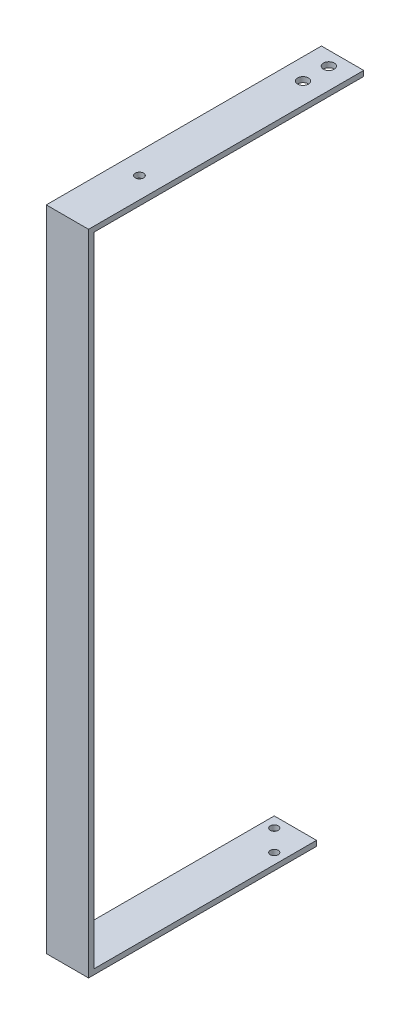
SolidWorks part; units mm, degrees
ref_plane "Alzado" through (0, 0, 0) normal (0, 0, 1) x (1, 0, 0)
ref_plane "Planta" through (0, 0, 0) normal (0, 1, 0) x (1, 0, 0)
ref_plane "Vista lateral" through (0, 0, 0) normal (1, 0, 0) x (0, 0, -1)
sketch "Croquis1" plane through (0, 0, 0) normal (0, 0, 1) x (1, 0, 0)
  line L1 (25.4, -3.155) -> (-25.4, -3.155)
  line L2 (25.4, -3.155) -> (25.4, 3.155)
  line L3 (25.4, 3.155) -> (-25.4, 3.155)
  line L4 (-25.4, -3.155) -> (-25.4, 3.155)
  line L5 (25.4, -3.155) -> (-25.4, 3.155) construction
  line L6 (25.4, 3.155) -> (-25.4, -3.155) construction
  point P0 (0, 0)
  dimension "D1" = 50.8
  dimension "D2" = 6.31
extrude "Saliente-Extruir1" add sketch "Croquis1" along normal blind 273.99
sketch "Croquis2" plane through (0, 3.155, 0) normal (0, 1, 0) x (1, 0, 0)
  line L0 (-25.4, -273.99) -> (25.4, -273.99)
  line L1 (25.4, -273.99) -> (25.4, -267.68)
  line L2 (25.4, -273.99) -> (25.4, 0) construction
  line L3 (25.4, -267.68) -> (-25.4, -267.68)
  line L4 (-25.4, -273.99) -> (-25.4, 0) construction
  line L5 (-25.4, -267.68) -> (-25.4, -273.99)
  dimension "D1" = 6.31
extrude "Saliente-Extruir2" add sketch "Croquis2" along normal blind 772.95
sketch "Croquis3" plane through (0, 0, 267.68) normal (0, 0, -1) x (-1, 0, 0)
  line L0 (25.4, 776.105) -> (25.4, 769.795)
  line L1 (25.4, 776.105) -> (25.4, 3.155) construction
  line L2 (25.4, 769.795) -> (-25.4, 769.795)
  line L3 (-25.4, 776.105) -> (-25.4, 3.155) construction
  line L4 (-25.4, 769.795) -> (-25.4, 776.105)
  line L5 (-25.4, 776.105) -> (25.4, 776.105)
  dimension "D1" = 6.31
extrude "Saliente-Extruir3" add sketch "Croquis3" along normal blind 324.39
sketch "Croquis4" plane through (0, -3.155, 0) normal (0, -1, 0) x (1, 0, 0)
  line L0 (25.4, 0) -> (-25.4, 0) construction
  line L1 (-25.4, 0) -> (-25.4, 50.8) construction
  line L2 (-25.4, 273.99) -> (-25.4, 0) construction
  line L3 (-25.4, 50.8) -> (25.4, 50.8) construction
  line L4 (25.4, 273.99) -> (25.4, 0) construction
  line L5 (25.4, 50.8) -> (25.4, 0) construction
  line L6 (25.4, 50.8) -> (-25.4, 0) construction
  line L7 (0, 25.4) -> (-25.4, 25.4) construction
  line L8 (-25.4, 25.4) -> (0, 25.4) construction
  line L9 (0, 25.4) -> (-25.4, 0) construction
  line L10 (-12.7, 12.7) -> (-20.119, 12.7) construction
  line L11 (0, 25.4) -> (25.4, 50.8) construction
  line L12 (12.7, 38.1) -> (6.0626, 38.1) construction
  circle A0 centre (-12.7, 12.7) radius 4.7625
  circle A1 centre (12.7, 38.1) radius 4.7625
  dimension "D2" = 9.525
  dimension "D3" = 9.525
  dimension "D1" = 50.8
extrude "Cortar-Extruir1" cut sketch "Croquis4" against normal blind 10
sketch "Croquis5" plane through (0, 776.105, 0) normal (0, 1, 0) x (1, 0, 0)
  line L0 (0, 56.71) -> (0, 40.21) construction
  line L1 (-25.4, 56.71) -> (25.4, 56.71) construction
  line L2 (0, 40.21) -> (0, 9.21) construction
  circle A0 centre (0, 40.21) radius 6.5
  circle A1 centre (0, 9.21) radius 6.5
  dimension "D3" = 13
  dimension "D4" = 13
  dimension "D1" = 16.5
  dimension "D2" = 31
extrude "Cortar-Extruir2" cut sketch "Croquis5" against normal blind 10
sketch "Croquis6" plane through (0, 776.105, 0) normal (0, 1, 0) x (1, 0, 0)
  line L0 (0, -273.99) -> (0, -231.39) construction
  line L1 (-25.4, -273.99) -> (25.4, -273.99) construction
  line L2 (0, -231.39) -> (0, -187.48) construction
  line L3 (0, -187.48) -> (0, -164.48) construction
  circle A0 centre (0, -231.39) radius 3.5 construction
  circle A1 centre (0, -187.48) radius 5
  circle A2 centre (0, -164.48) radius 3.5 construction
  dimension "D4" = 7
  dimension "D5" = 10
  dimension "D6" = 7
  dimension "D1" = 86.51
  dimension "D3" = 23
extrude "Cortar-Extruir3" cut sketch "Croquis6" against normal blind 35
